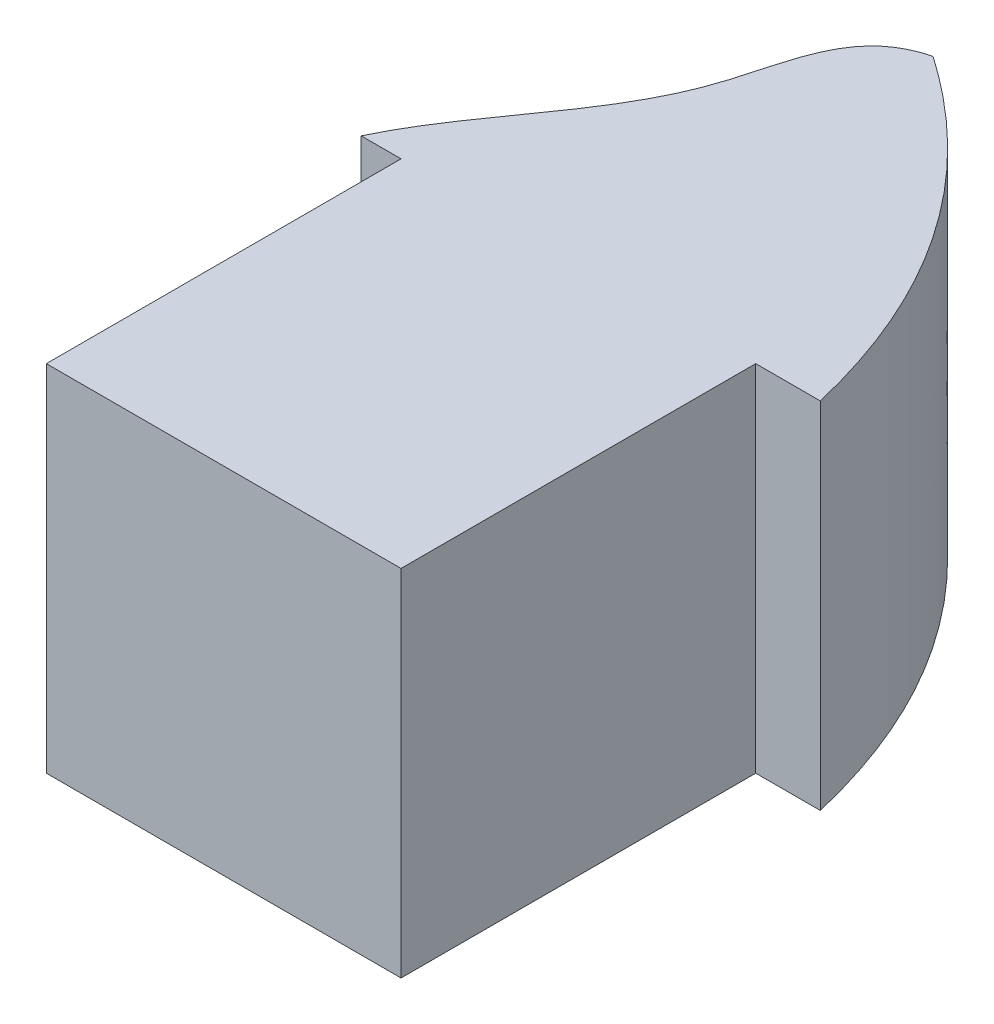
SolidWorks part; units mm, degrees
ref_plane "Front Plane" through (0, 0, 0) normal (0, 0, 1) x (1, 0, 0)
ref_plane "Top Plane" through (0, 0, 0) normal (0, 1, 0) x (1, 0, 0)
ref_plane "Right Plane" through (0, 0, 0) normal (1, 0, 0) x (0, 0, -1)
sketch "Sketch1" plane through (0, 0, 0) normal (0, 0, 1) x (1, 0, 0)
  line L1 (32.7421, 8.6286) -> (35.9171, 8.6286)
  line L2 (32.7421, 8.6286) -> (32.7421, 5.4536)
  line L3 (32.7421, 5.4536) -> (35.9171, 5.4536)
  line L4 (35.9171, 8.6286) -> (35.9171, 5.4536)
  dimension "D1" = 3.175
  dimension "D2" = 3.175
extrude "Boss-Extrude1" add sketch "Sketch1" against normal blind 6.35 contours L4 L3 L2 L1
sketch "Sketch2" plane through (0, 5.4536, 0) normal (0, -1, 0) x (1, 0, 0)
  line L0 (0, -3.175) -> (57.2083, -3.175) construction
  line L1 (31.1546, -3.175) -> (37.5046, -3.175)
  line L2 (31.1546, -3.175) -> (31.1546, -6.35)
  line L3 (31.1546, -6.35) -> (37.5046, -6.35)
  line L4 (37.5046, -3.175) -> (37.5046, -6.35)
  line L5 (32.7421, -6.35) -> (32.7421, 0) construction
  line L6 (35.9171, -6.35) -> (35.9171, 0) construction
  dimension "D1" = 3.175
  dimension "D2" = 1.5875
  dimension "D3" = 1.5875
extrude "Boss-Extrude2" add sketch "Sketch2" against normal blind 3.175
sketch "Sketch3" plane through (0, 5.4536, 0) normal (0, -1, 0) x (1, 0, 0)
  line L0 (37.5046, -3.175) -> (35.9171, -3.175) construction
  line L1 (31.1546, -6.35) -> (37.5046, -6.35) construction
  line L2 (32.7421, -3.175) -> (31.1546, -3.175) construction
  line L4 (30.2776, -3.175) -> (37.8039, -3.175)
  line L5 (30.2776, -3.175) -> (30.2776, -6.6203)
  line L6 (30.2776, -6.6203) -> (37.8039, -6.6203)
  line L7 (37.8039, -3.175) -> (37.8039, -6.6203)
  spline S0 degree 2 poles (36.4953, -3.175) (36.021, -5.1748) (34.3296, -6.35) knots 0 0 0 1 1 1
  spline S1 degree 3 poles (32.3854, -3.175) (32.7188, -3.8784) (33.6903, -4.7594) (33.7566, -6.2111) (34.3296, -6.35) knots 0 0 0 0 0.611532 1 1 1 1
  line M5 (31.1546, -3.175) -> (31.1546, -6.35)
  line M6 (31.1546, -6.35) -> (37.5046, -6.35)
  line M7 (37.5046, -6.35) -> (37.5046, -3.175)
  line M8 (37.5046, -3.175) -> (35.9171, -3.175)
extrude "Cut-Extrude1" cut sketch "Sketch3" against normal through all contours S1 L4 M5 M6 | S0 M8 M6 M7 | L7 L4 L5 L6 M7 M6 M5
